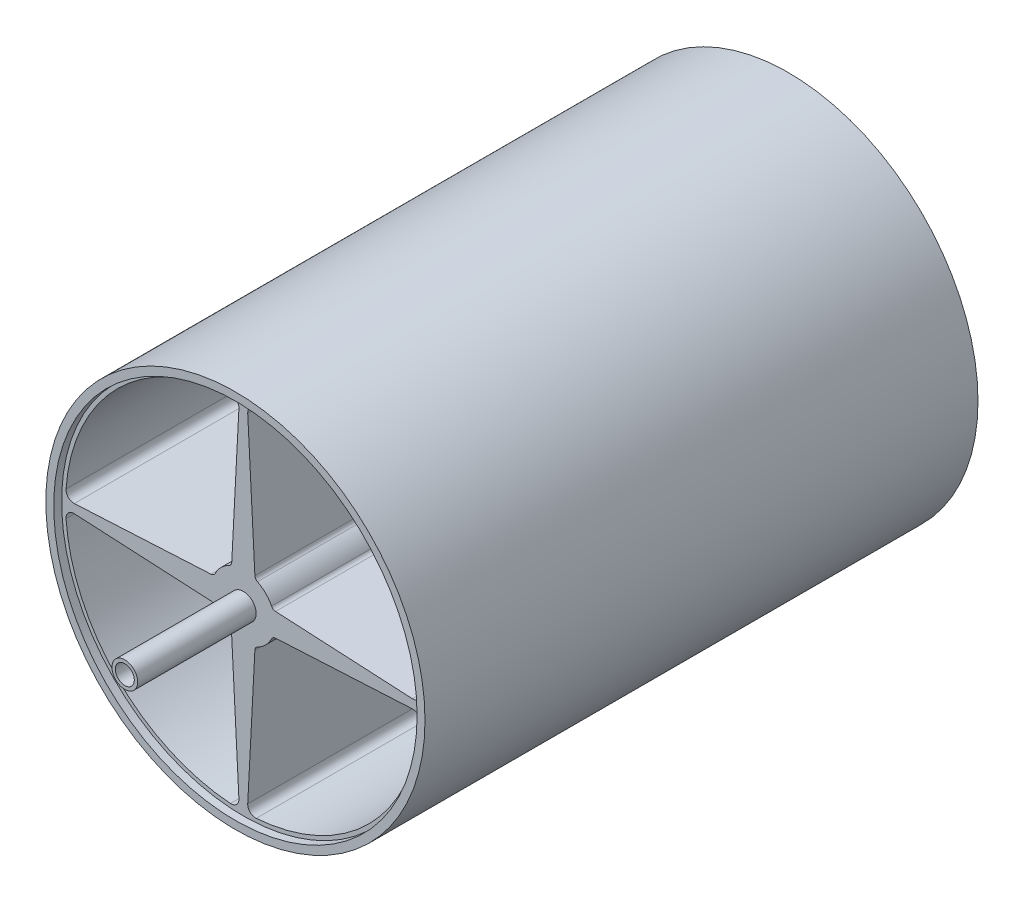
SolidWorks part; units mm, degrees
ref_plane "Front Plane" through (0, 0, 0) normal (0, 0, 1) x (1, 0, 0)
ref_plane "Top Plane" through (0, 0, 0) normal (0, 1, 0) x (1, 0, 0)
ref_plane "Right Plane" through (0, 0, 0) normal (1, 0, 0) x (0, 0, -1)
sketch "Sketch1" plane through (0, 0, 0) normal (0, 0, 1) x (1, 0, 0)
  circle A0 centre (0, 0) radius 240
extrude "Boss-Extrude1" add sketch "Sketch1" along normal blind 700
sketch "Sketch2" plane through (0, 0, 700) normal (0, 0, 1) x (1, 0, 0)
  circle A0 centre (0, 0) radius 230
extrude "Cut-Extrude1" cut sketch "Sketch2" against normal blind 10
sketch "Sketch3" plane through (0, 0, 0) normal (0, 0, -1) x (-1, 0, 0)
  circle A0 centre (0, 0) radius 230
extrude "Cut-Extrude2" cut sketch "Sketch3" against normal blind 10
sketch "Sketch4" plane through (0, 0, 690) normal (0, 0, 1) x (1, 0, 0)
  line L0 (0, 225) -> (0, -225) construction
  line L1 (-225, 0) -> (225, 0) construction
  line L2 (-5.5782, 213.9125) -> (-14.6509, 40.7941)
  line L3 (5.5782, 213.9125) -> (14.6509, 40.7941)
  line L4 (-213.9125, 5.5782) -> (-40.7941, 14.6509)
  line L5 (-213.9125, -5.5782) -> (-40.7941, -14.6509)
  line L6 (213.9125, -5.5782) -> (40.7941, -14.6509)
  line L7 (213.9125, 5.5782) -> (40.7941, 14.6509)
  line L8 (5.5782, -213.9125) -> (14.6509, -40.7941)
  line L9 (-5.5782, -213.9125) -> (-14.6509, -40.7941)
  arc A0 (-16.2884, 224.4096) -> (-224.4096, 16.2884) centre (0, 0) ccw
  arc A1 (-17.9502, 35.7462) -> (-35.7462, 17.9502) centre (0, 0) ccw
  arc A2 (-35.7462, -17.9502) -> (-17.9502, -35.7462) centre (0, 0) ccw
  arc A3 (35.7462, 17.9502) -> (17.9502, 35.7462) centre (0, 0) ccw
  arc A4 (17.9502, -35.7462) -> (35.7462, -17.9502) centre (0, 0) ccw
  arc A5 (-224.4096, -16.2884) -> (-16.2884, -224.4096) centre (0, 0) ccw
  arc A6 (16.2884, -224.4096) -> (224.4096, -16.2884) centre (0, 0) ccw
  arc A7 (224.4096, 16.2884) -> (16.2884, 224.4096) centre (0, 0) ccw
  arc A8 (17.9502, 35.7462) -> (14.6509, 40.7941) centre (20.6427, 41.1081) cw
  arc A9 (40.7941, 14.6509) -> (35.7462, 17.9502) centre (41.1081, 20.6427) cw
  arc A10 (35.7462, -17.9502) -> (40.7941, -14.6509) centre (41.1081, -20.6427) cw
  arc A11 (17.9502, -35.7462) -> (14.6509, -40.7941) centre (20.6427, -41.1081) ccw
  arc A12 (-17.9502, -35.7462) -> (-14.6509, -40.7941) centre (-20.6427, -41.1081) cw
  arc A13 (-35.7462, -17.9502) -> (-40.7941, -14.6509) centre (-41.1081, -20.6427) ccw
  arc A14 (-35.7462, 17.9502) -> (-40.7941, 14.6509) centre (-41.1081, 20.6427) cw
  arc A15 (-14.6509, 40.7941) -> (-17.9502, 35.7462) centre (-20.6427, 41.1081) cw
  arc A16 (224.4096, -16.2884) -> (213.9125, -5.5782) centre (214.4359, -15.5645) ccw
  arc A17 (224.4096, 16.2884) -> (213.9125, 5.5782) centre (214.4359, 15.5645) cw
  arc A18 (16.2884, -224.4096) -> (5.5782, -213.9125) centre (15.5645, -214.4359) cw
  arc A19 (-16.2884, -224.4096) -> (-5.5782, -213.9125) centre (-15.5645, -214.4359) ccw
  arc A20 (-224.4096, -16.2884) -> (-213.9125, -5.5782) centre (-214.4359, -15.5645) cw
  arc A21 (-213.9125, 5.5782) -> (-224.4096, 16.2884) centre (-214.4359, 15.5645) cw
  arc A22 (16.2884, 224.4096) -> (5.5782, 213.9125) centre (15.5645, 214.4359) ccw
  arc A23 (-16.2884, 224.4096) -> (-5.5782, 213.9125) centre (-15.5645, 214.4359) cw
  point P24 (14.8422, 37.1444)
  point P27 (37.1444, 14.8422)
  point P30 (37.1444, -14.8422)
  point P33 (14.8422, -37.1444)
  point P36 (-14.8422, -37.1444)
  point P39 (-37.1444, -14.8422)
  point P42 (-37.1444, 14.8422)
  point P45 (-14.8422, 37.1444)
  point P48 (224.9444, -5)
  point P51 (224.9444, 5)
  point P54 (5, -224.9444)
  point P57 (-5, -224.9444)
  point P60 (-224.9444, -5)
  point P63 (-224.9444, 5)
  point P66 (5, 224.9444)
  point P69 (-5, 224.9444)
  dimension "D1" = 450
  dimension "D2" = 80
  dimension "D7" = 5
  dimension "D11" = 6
  dimension "D12" = 10
  dimension "D3" = 5
  dimension "D4" = 3
  dimension "D5" = 5
  dimension "D6" = 3
  dimension "D8" = 5
  dimension "D9" = 3
  dimension "D10" = 3
extrude "Cut-Extrude3" cut sketch "Sketch4" against normal up to next
sketch "Sketch5" plane through (0, 0, 690) normal (0, 0, 1) x (1, 0, 0)
  circle A0 centre (0, 0) radius 16.25
  dimension "D1" = 32.5
extrude "Boss-Extrude2" add sketch "Sketch5" along normal blind 150
sketch "Sketch6" plane through (0, 0, 10) normal (0, 0, -1) x (-1, 0, 0)
  circle A0 centre (0, 0) radius 16.25
  dimension "D1" = 32.5
extrude "Boss-Extrude3" add sketch "Sketch6" along normal blind 150 contours A0
sketch "Sketch7" plane through (0, 0, 840) normal (0, 0, 1) x (1, 0, 0)
  line L0 (0, 16.25) -> (0, -16.25) construction
  line L1 (-16.25, 0) -> (16.25, 0) construction
  circle A0 centre (0, 0) radius 12
  circle A1 centre (0, 0) radius 16.25 construction
  circle A2 centre (0, 0) radius 16.25 construction
  dimension "D1" = 24
extrude "Cut-Extrude4" cut sketch "Sketch7" against normal blind 50
sketch "Sketch8" plane through (0, 0, -140) normal (0, 0, -1) x (-1, 0, 0)
  circle A0 centre (0, 0) radius 12
  dimension "D1" = 24
extrude "Cut-Extrude5" cut sketch "Sketch8" against normal blind 50
sketch "Sketch10" plane through (0, 0, -140) normal (0, 0, -1) x (-1, 0, 0)
  line L0 (0, 16.25) -> (0, -16.25) construction
  line L1 (-4, 11.3137) -> (-4, 15.0037)
  line L2 (-4, 15.0037) -> (4, 15.0037)
  line L3 (4, 15.0037) -> (4, 11.3137)
  arc A0 (4, 11.3137) -> (-4, 11.3137) centre (0, 0) ccw
  circle A1 centre (0, 0) radius 16.25 construction
  dimension "D1" = 24
  dimension "D2" = 4
  dimension "D3" = 4
  dimension "D4" = 3.69
extrude "Cut-Extrude8" cut sketch "Sketch10" against normal blind 45
